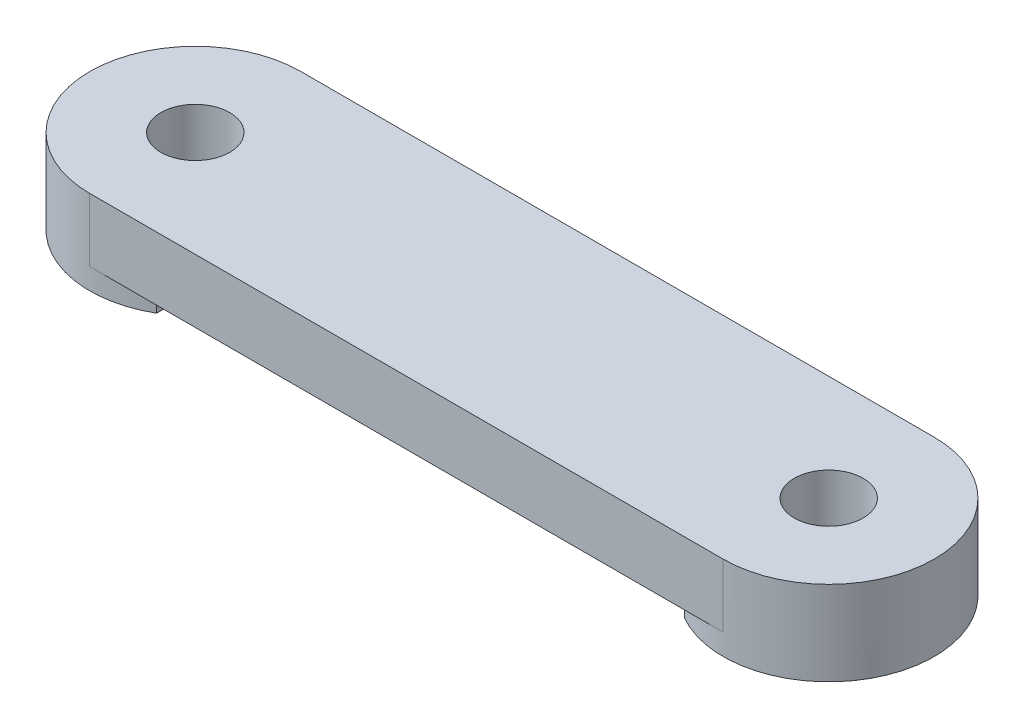
SolidWorks part; units mm, degrees
material "ABS"
ref_plane "Front" through (0, 0, 0) normal (0, 0, 1) x (1, 0, 0)
ref_plane "Top" through (0, 0, 0) normal (0, 1, 0) x (1, 0, 0)
ref_plane "Right" through (0, 0, 0) normal (1, 0, 0) x (0, 0, -1)
sketch "Sketch1" plane through (0, 0, 0) normal (0, 1, 0) x (1, 0, 0)
  line L0 (-15, 0) -> (15, 0) construction
  circle A0 centre (-15, 0) radius 5
  circle A1 centre (15, 0) radius 5
  point P4 (0, 0)
  dimension "D2" = 10
  dimension "D1" = 30
extrude "Boss-Extrude1" add sketch "Sketch1" along normal blind 1
sketch "Sketch2" plane through (0, 1, 0) normal (0, 1, 0) x (1, 0, 0)
  line L0 (-15, -5) -> (15, -5)
  line L1 (15, 5) -> (-15, 5)
  circle A0 centre (-15, 0) radius 5 construction
  circle A1 centre (15, 0) radius 5
  arc A2 (15, -5) -> (15, 5) centre (15, 0) ccw
  arc A3 (-15, 5) -> (-15, -5) centre (-15, 0) ccw
  dimension "D1" = 0
extrude "Boss-Extrude2" add sketch "Sketch2" along normal blind 3
hole_wizard "#4 Clearance Hole1" positions "Sketch3" profile "Sketch4" hole size "#4" standard "ANSI Inch" end condition through all
sketch "Sketch3" plane through (0, 4, 0) normal (0, 1, 0) x (1, 0, 0)
  point P0 (-15, 0)
  point P3 (15, 0)
sketch "Sketch4" plane through (-15, 4, 0) normal (1, 0, 0) x (0, 0, 1)
  line L0 (0, 0) -> (0, 4)
  line L1 (0, 4) -> (1.6319, 4)
  line L2 (1.6319, 4) -> (1.6319, 0)
  line L5 (1.6319, 0) -> (0, 0)
  line L11 (0, -6.35) -> (0, 107.95) construction
  dimension "Thru Hole Dia." = 3.2639
  dimension "Thru Hole Depth" = 4
sketch "Sketch5" plane through (0, 0, 0) normal (0, -1, 0) x (1, 0, 0)
  line L0 (-9.5, 3) -> (9.5, 3) construction
  line L1 (12.5, 3) -> (12.5, 6)
  line L2 (9.5, 0) -> (6.5, 0)
  line L3 (6.5, 0) -> (6.5, 3)
  line L4 (12.5, 6) -> (9.5, 6)
  line L5 (-12.5, 3) -> (-12.5, 6)
  line L6 (-12.5, 6) -> (-9.5, 6)
  line L7 (-9.5, 0) -> (-6.5, 0)
  line L8 (-6.5, 0) -> (-6.5, 3)
  arc A0 (-6.5, 3) -> (-9.5, 6) centre (-9.5, 3) ccw
  arc A1 (9.5, 6) -> (6.5, 3) centre (9.5, 3) ccw
  arc A2 (-12.5, 3) -> (-9.5, 0) centre (-9.5, 3) ccw
  arc A3 (9.5, 0) -> (12.5, 3) centre (9.5, 3) ccw
  point P4 (0, 3)
  dimension "D1" = 6
  dimension "D2" = 19
  dimension "D3" = 3
extrude "Cut-Extrude1" cut sketch "Sketch5" against normal up to surface (1 mm away) up to face at (0, 1, 0)
